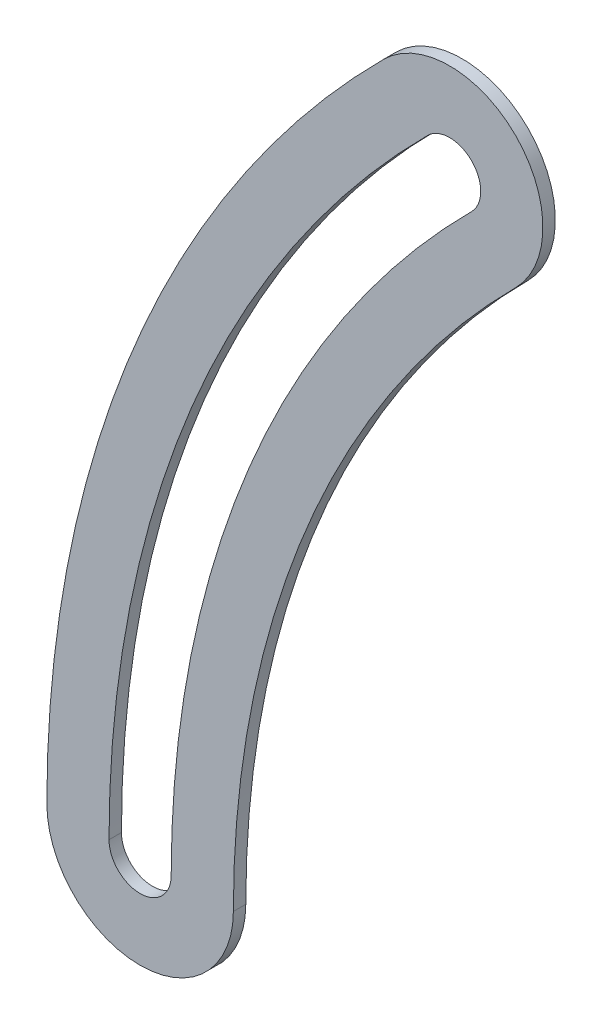
SolidWorks part; units mm, degrees
ref_plane "Спереди" through (0, 0, 0) normal (0, 0, 1) x (1, 0, 0)
ref_plane "Сверху" through (0, 0, 0) normal (0, 1, 0) x (1, 0, 0)
ref_plane "Справа" through (0, 0, 0) normal (1, 0, 0) x (0, 0, -1)
sketch "Эскиз1" plane through (0, 0, 0) normal (0, 0, 1) x (1, 0, 0)
  arc A6 (-60.1041, 60.1041) -> (-85, 0) centre (0, 0) ccw construction
  arc A11 (-65.4074, 65.4074) -> (-92.5, 0) centre (0, 0) ccw
  arc A12 (-54.8008, 54.8008) -> (-77.5, 0) centre (0, 0) ccw
  arc A13 (-54.8008, 54.8008) -> (-65.4074, 65.4074) centre (-60.1041, 60.1041) ccw
  arc A14 (-92.5, 0) -> (-77.5, 0) centre (-85, 0) ccw
  arc A15 (-60.1041, 60.1041) -> (-85, 0) centre (0, 0) ccw construction
  arc A16 (-61.8718, 61.8718) -> (-87.5, 0) centre (0, 0) ccw
  arc A17 (-58.3363, 58.3363) -> (-82.5, 0) centre (0, 0) ccw
  arc A18 (-58.3363, 58.3363) -> (-61.8718, 61.8718) centre (-60.1041, 60.1041) ccw
  arc A19 (-87.5, 0) -> (-82.5, 0) centre (-85, 0) ccw
  point P5 (-78.5298, 32.5281)
  point P11 (-78.5298, 32.5281)
  point P16 (0, 0)
extrude "Бобышка-Вытянуть1" add sketch "Эскиз1" along normal blind 1
